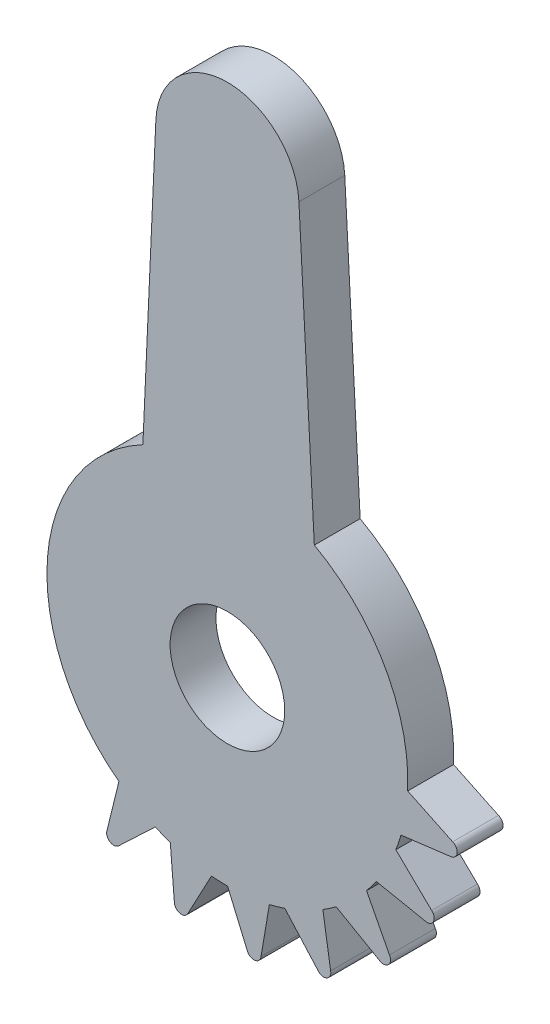
SolidWorks part; units mm, degrees
ref_plane "Front Plane" through (0, 0, 0) normal (0, 0, 1) x (1, 0, 0)
ref_plane "Top Plane" through (0, 0, 0) normal (0, 1, 0) x (1, 0, 0)
ref_plane "Right Plane" through (0, 0, 0) normal (1, 0, 0) x (0, 0, -1)
sketch "Sketch4" plane through (0, 0, 0) normal (0, 0, 1) x (1, 0, 0)
  line L1 (21.0679, 33.3251) -> (19.993, 53.5478)
  line L2 (9.0984, 33.4149) -> (10.0022, 53.4268)
  arc A0 (9.0984, 33.4149) -> (21.0679, 33.3251) centre (15, 22.2825) ccw
  arc A1 (19.993, 53.5478) -> (10.0022, 53.4268) centre (15.0001, 53.2825) ccw
  circle A2 centre (15, 22.2825) radius 4
  dimension "D1" = 25.2
  dimension "D4" = 10
  dimension "D2" = 8
extrude "Boss-Extrude4" add sketch "Sketch4" along normal blind 3.2
sketch "Sketch5" plane through (0, 0, 0) normal (0, 0, 1) x (1, 0, 0)
  line L0 (15, 22.2825) -> (-7.1883, 22.2825) construction
  line L2 (2.4862, 23.7537) -> (-0.8545, 22.7714)
  line L4 (2.4858, 20.8147) -> (-0.8545, 21.7935)
  arc A0 (-0.8545, 22.7714) -> (-0.8545, 21.7935) centre (-0.75, 22.2825) ccw
  arc A1 (2.4862, 23.7537) -> (2.4858, 20.8147) centre (15, 22.2825) ccw
  dimension "D1" = 1
  dimension "D3" = 12.6
  dimension "D2" = 15.75
extrude "Boss-Extrude5" [suppressed] add sketch "Sketch5" along normal blind 3.2
pattern_circular "CirPattern1" [suppressed] count 2 every 18.5
sketch "Sketch6" plane through (0, 0, 3.2) normal (0, 0, 1) x (1, 0, 0)
  line L0 (27.5874, 21.7195) -> (30.7269, 20.2166)
  line L1 (27.1146, 18.8188) -> (30.5452, 19.2508)
  arc A0 (27.1146, 18.8188) -> (27.5874, 21.7195) centre (15, 22.2825) ccw
  arc A1 (30.5452, 19.2508) -> (30.7269, 20.2166) centre (30.5452, 19.7508) ccw
extrude "Boss-Extrude6" add sketch "Sketch6" against normal blind 3.2
pattern_circular "CirPattern3" count 7 every 18.5 about axis through (15, 22.2825, 0) along (0, 0, 1) of "Boss-Extrude6"
